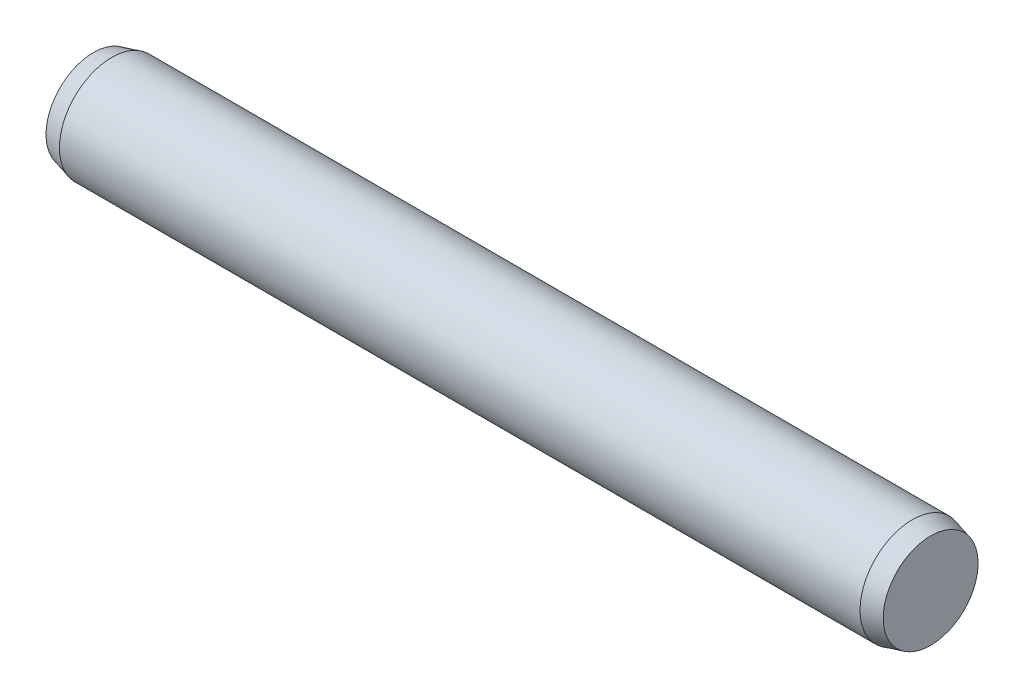
SolidWorks part; units mm, degrees
ref_plane "Plane1" through (0, 0, 0) normal (0, 0, 1) x (1, 0, 0)
ref_plane "Plane2" through (0, 0, 0) normal (0, 1, 0) x (1, 0, 0)
ref_plane "Plane3" through (0, 0, 0) normal (1, 0, 0) x (0, 0, -1)
other "Configuration Table"
sketch "Sketch1" plane through (0, 0, 0) normal (0, 0, 1) x (1, 0, 0)
  line L1 (-6.35, 0) -> (107.95, 0) construction
  line L2 (0, 0) -> (16, 0)
  line L3 (16, 0) -> (16, 0.9062)
  line L4 (16, 0.9062) -> (15.65, 1)
  line L5 (15.65, 1) -> (0.35, 1)
  line L6 (0, 0.9062) -> (0, 0)
  line L7 (0, 0.9062) -> (0.35, 1)
  dimension "Chamfer_len" = 0.35
  dimension "D3" = 15
  dimension "Diameter" = 2
  dimension "D1" = 0.35
  dimension "D2" = 15
  dimension "Length" = 16
revolve "Base-Revolve" add sketch "Sketch1" angle 360 about L1
equation "\"D3@Sketch1\" = 15.0"
equation "\"D1@Sketch1\" = \"Chamfer_len@Sketch1\""
equation "\"D2@Sketch1\" = \"D3@Sketch1\""
